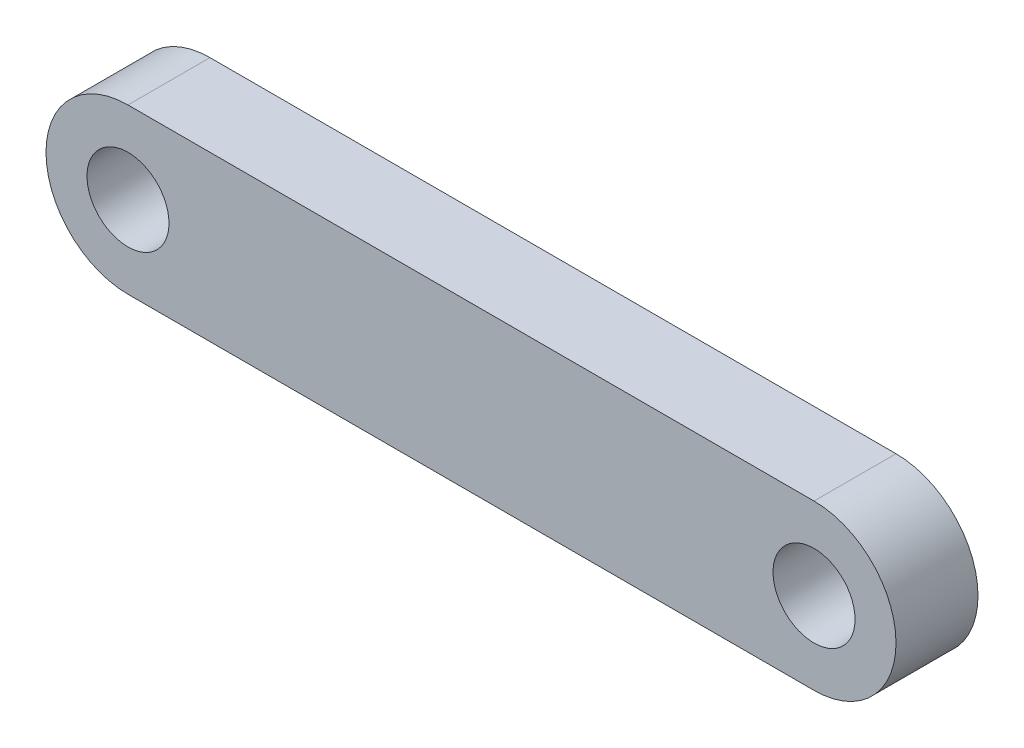
SolidWorks part; units mm, degrees
ref_plane "Plano frontal" through (0, 0, 0) normal (0, 0, 1) x (1, 0, 0)
ref_plane "Plano superior" through (0, 0, 0) normal (0, 1, 0) x (1, 0, 0)
ref_plane "Plano direito" through (0, 0, 0) normal (1, 0, 0) x (0, 0, -1)
sketch "Esboço1" plane through (0, 0, 0) normal (0, 0, 1) x (1, 0, 0)
  line L0 (-20.92, 5) -> (20.92, 5)
  line L1 (-29.2846, 0) -> (29.6301, 0) construction
  line L2 (-20.92, -5) -> (20.92, -5)
  arc A0 (-20.92, 5) -> (-20.92, -5) centre (-20.92, 0) ccw
  arc A1 (20.92, 5) -> (20.92, -5) centre (20.92, 0) cw
  circle A2 centre (-20.92, 0) radius 2.5
  circle A3 centre (20.92, 0) radius 2.5
  point P3 (0, 5)
  dimension "D1" = 5
  dimension "D2" = 41.84
extrude "Ressalto-extrusão1" add sketch "Esboço1" along normal blind 5
